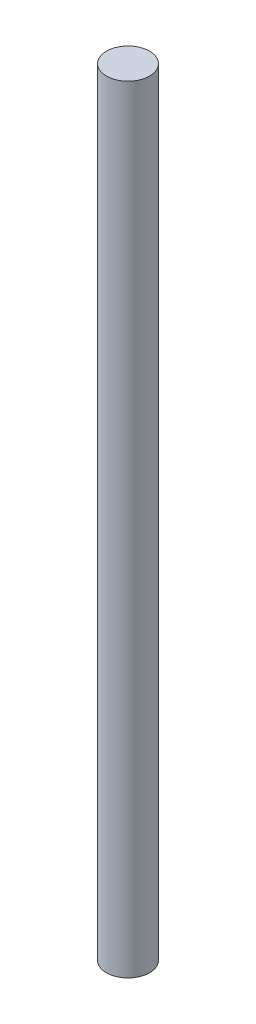
SolidWorks part; units mm, degrees
ref_plane "前视基准面" through (0, 0, 0) normal (0, 0, 1) x (1, 0, 0)
ref_plane "上视基准面" through (0, 0, 0) normal (0, 1, 0) x (1, 0, 0)
ref_plane "右视基准面" through (0, 0, 0) normal (1, 0, 0) x (0, 0, -1)
sketch "草图1" plane through (0, 0, 0) normal (0, 1, 0) x (1, 0, 0)
  circle A0 centre (0, 0) radius 2.5
  dimension "D1" = 5
extrude "凸台-拉伸1" add sketch "草图1" along normal blind 90
